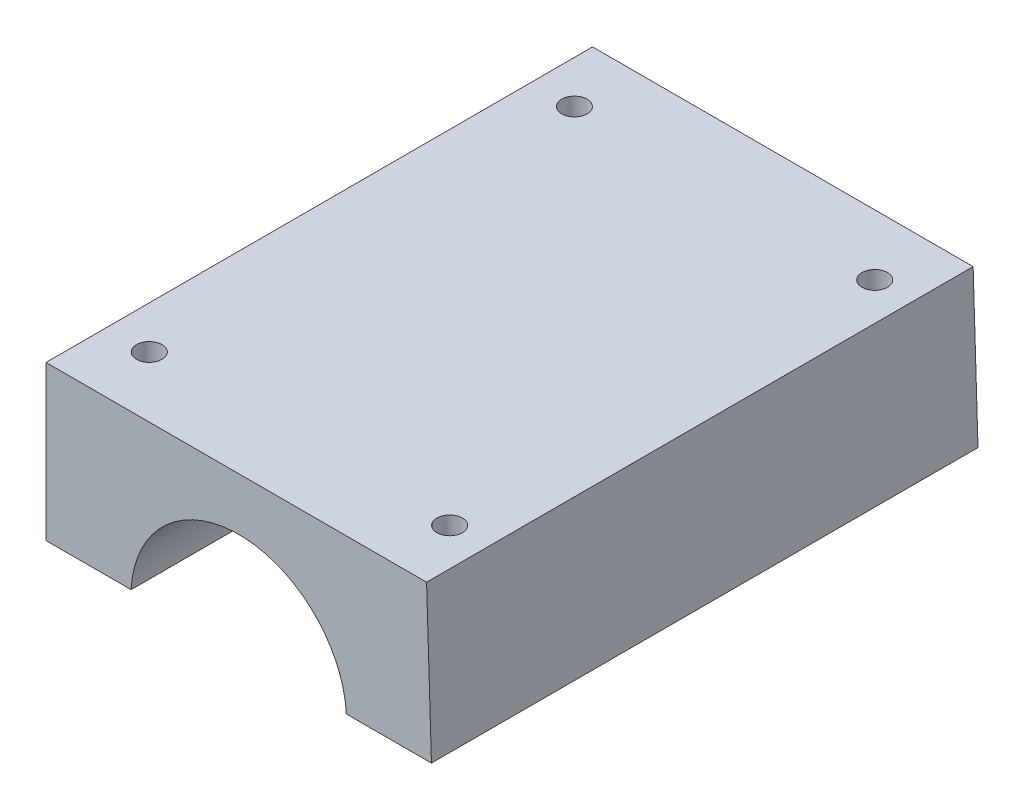
SolidWorks part; units mm, degrees
ref_plane "Front" through (0, 0, 0) normal (0, 0, 1) x (1, 0, 0)
ref_plane "Top" through (0, 0, 0) normal (0, 1, 0) x (1, 0, 0)
ref_plane "Right" through (0, 0, 0) normal (1, 0, 0) x (0, 0, -1)
sketch "Sketch1" plane through (0, 0, 0) normal (0, 0, 1) x (1, 0, 0)
  line L0 (-31.75, 0) -> (31.75, 0) construction
  line L1 (-31.7342, 1) -> (-17.7218, 1)
  line L2 (-31.75, 1) -> (31.75, 1) construction
  line L3 (17.7218, 1) -> (31.7342, 1)
  arc A0 (31.7342, 1) -> (-31.7342, 1) centre (0, 0) ccw
  arc A1 (17.7218, 1) -> (-17.7218, 1) centre (0, 0) ccw
  dimension "D1" = 35.5
  dimension "D2" = 63.5
  dimension "D3" = 1
extrude "Boss-Extrude1" add sketch "Sketch1" along normal blind 90
sketch "Sketch4" plane through (0, 0, 0) normal (0, 0, -1) x (-1, 0, 0)
  line L0 (-31.7342, 1) -> (-30.7653, 31.75)
  line L1 (-30.7653, 31.75) -> (0, 31.75)
  line L2 (0, 31.75) -> (31.7342, 31.75)
  line L3 (31.7342, 1) -> (31.7342, 31.75)
  arc A0 (31.7342, 1) -> (-31.7342, 1) centre (0, 0) ccw construction
  arc A1 (31.7342, 1) -> (-31.7342, 1) centre (0, 0) ccw
  arc M1 (31.7342, 1) -> (-31.7342, 1) centre (0, 0) ccw
extrude "Boss-Extrude2" add sketch "Sketch4" against normal up to surface (90 mm away) contours L1 L0 M1 | L3 L2 M1 up to face at (0, 12.875, 90)
sketch "Sketch5" plane through (0, 0, 90) normal (0, 0, 1) x (1, 0, 0)
  line L0 (31.7342, 1) -> (30.7653, 31.75) construction
  line L1 (-31.7342, 31.75) -> (30.9339, 31.75)
  line L2 (-31.7342, 31.75) -> (-31.7342, 26.4)
  line L3 (-31.7342, 26.4) -> (30.9339, 26.4)
  line L4 (30.9339, 31.75) -> (30.9339, 26.4)
  line L5 (-31.7342, 31.75) -> (30.9339, 26.4) construction
  line L6 (-31.7342, 26.4) -> (30.9339, 31.75) construction
  line L7 (17.7218, 1) -> (31.7342, 1) construction
  point P4 (-0.4002, 29.075)
  point P8 (-9.8373, 21.8897)
  dimension "D1" = 25.4
extrude "Cut-Extrude1" cut sketch "Sketch5" against normal up to next
sketch "Sketch2" plane through (0, 1, 0) normal (0, -1, 0) x (-1, 0, 0)
  line L0 (24.728, -90) -> (24.728, 0) construction
  line L1 (31.7342, -90) -> (17.7218, -90) construction
  line L2 (31.7342, 0) -> (17.7218, 0) construction
  line L3 (-24.728, -90) -> (-24.728, 0) construction
  line L4 (-17.7218, -90) -> (-31.7342, -90) construction
  line L5 (-17.7218, 0) -> (-31.7342, 0) construction
  line L6 (0, -90) -> (0, 0) construction
  line L7 (-17.7218, -90) -> (17.7218, -90) construction
  circle A0 centre (24.728, -80) radius 1
  circle A1 centre (24.728, -10) radius 1
  circle A2 centre (-24.728, -10) radius 1
  circle A3 centre (-24.728, -80) radius 1
  dimension "D1" = 10
  dimension "D2" = 10
  dimension "D3" = 2
hole_wizard "Tap Drill for M5x0.8 Tap1" positions "3DSketch1" profile "Sketch3" hole size "M5x0.8" standard "ANSI Metric" end condition up to next
sketch3d "3DSketch1"
  point P0 (-24.728, 1, 80)
  point P3 (-24.728, 1, 10)
  point P6 (24.728, 1, 80)
  point P9 (24.728, 1, 10)
sketch "Sketch3" plane through (-24.728, 1, 80) normal (1, 0, 0) x (0, 0, -1)
  line L0 (0, 0) -> (0, 25.4)
  line L1 (0, 25.4) -> (2.1, 25.4)
  line L2 (2.1, 25.4) -> (2.1, 0)
  line L5 (2.1, 0) -> (0, 0)
  line L11 (0, -6.35) -> (0, 107.95) construction
  dimension "Thru Hole Dia." = 4.2
  dimension "Thru Hole Depth" = 25.4
